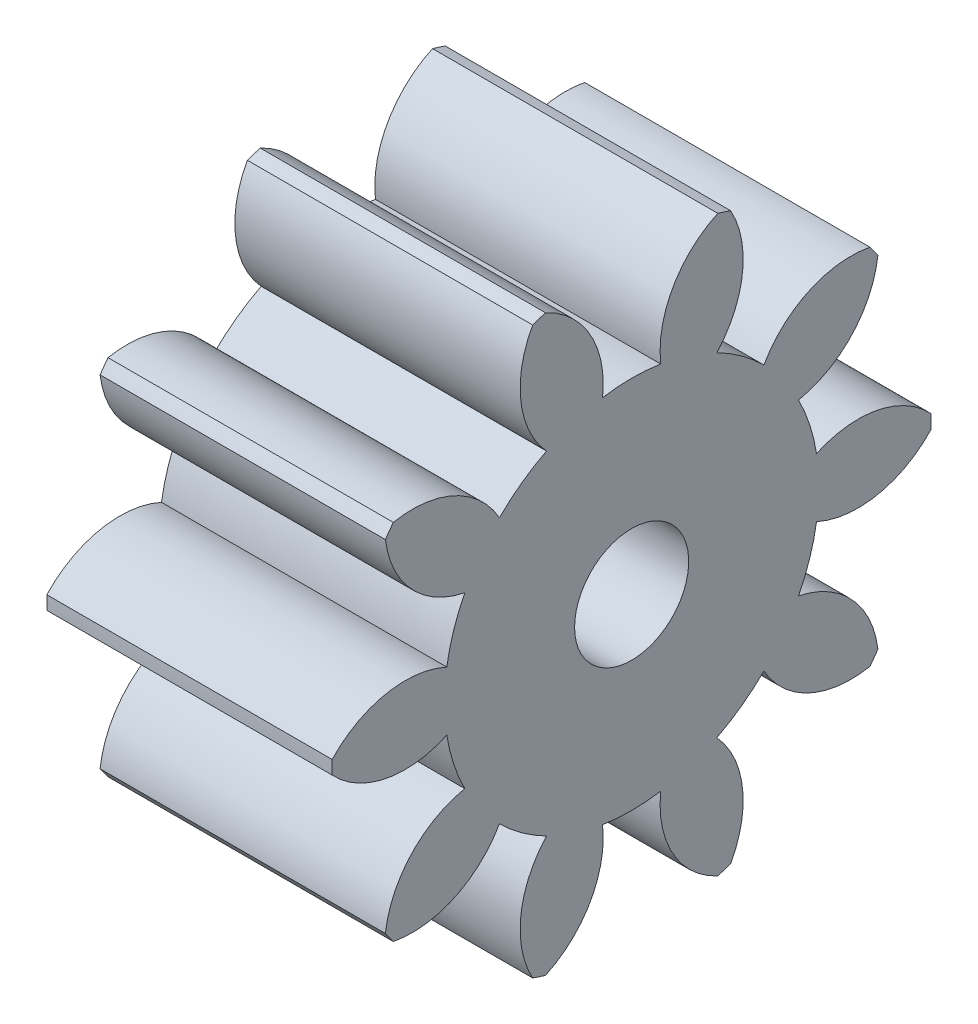
SolidWorks part; units mm, degrees
ref_plane "Plane1" through (0, 0, 0) normal (0, 0, 1) x (1, 0, 0)
ref_plane "Plane2" through (0, 0, 0) normal (0, 1, 0) x (1, 0, 0)
ref_plane "Plane3" through (0, 0, 0) normal (1, 0, 0) x (0, 0, -1)
sketch "HoldingSke" plane through (0, 0, 0) normal (0, 1, 0) x (1, 0, 0)
  line L0 (0, 0) -> (0.5627, -0.0992)
  line L1 (-15, 0) -> (100, 0) construction
  line L2 (0, 0) -> (-2.1039, 2.3779)
  line L3 (0, 0) -> (-11.863, 4.5341)
  line L4 (0, 0) -> (8.5048, 1.4996)
  line L5 (0, 0) -> (-46.8476, -17.4728)
  line L6 (0, 0) -> (-8.2896, -5.593)
  line L7 (-2.1039, 2.3779) -> (8.6586, 51.2059)
  line L8 (-76.2, 54.61) -> (-75.5, 54.61)
  line L9 (-71.009, 38.7566) -> (-53.1078, 45.2721)
  line L10 (-76.2, 71.12) -> (104.1128, 71.12)
  line L11 (0, 0) -> (-10, 0)
  line L12 (-76.2, 101.6) -> (-76.147, 101.6)
  line L13 (24.9733, 27.94) -> (52.9518, 28.4284)
  line L14 (24.9733, 27.94) -> (24.9743, 27.94)
  line L15 (24.9733, 27.94) -> (100.4006, 29.5858)
  line L16 (-63.627, -1.75) -> (-12.827, -1.75)
  circle A0 centre (0, 0) radius 2
  circle A1 centre (0, 0) radius 6.5615
  circle A2 centre (0, 0) radius 37.5
  circle A3 centre (0, 0) radius 2
  dimension "MHD" = 13.123
  dimension "Hub_dia" = 75
  dimension "Bore" = 4
  dimension "MBD" = 4
  dimension "Num_teeth" = 10
  dimension "Pitch" = 0.5714
  dimension "Overall_len" = 50
  dimension "Show_teeth" = 10
  dimension "Thickness" = 10
  dimension "OAL" = 50.0001
  dimension "T_dim" = 0.7
  dimension "Ap" = 20
  dimension "H" = 19.05
  dimension "Pitch_radius" = 180.3128
  dimension "Width" = 10
  dimension "Backlash" = 0.053
  dimension "Addendum_fac" = 1
  dimension "Dedendum_fac" = 1.25
  dimension "Clearance_fac" = 0.25
  dimension "Dedendum_add" = 0.001
  dimension "Module" = 1.75
sketch "BasProSke" plane through (0, 0, 0) normal (0, 1, 0) x (1, 0, 0)
  line L0 (-10, 0) -> (60, 0) construction
  line L1 (0, 0) -> (0, 10.5)
  line L2 (0, 0) -> (10, 0)
  line L3 (10, 0) -> (10, 10.5)
  line L4 (10, 10.5) -> (0, 10.5)
  dimension "Thickness" = 10
  dimension "Diameter" = 21
revolve "Base-Revolve" add sketch "BasProSke" angle 360 about L0
sketch "TooCutSke" plane through (0, 0, 0) normal (1, 0, 0) x (0, 0, -1)
  line L1 (0, 0) -> (0, 107) construction
  line L2 (0, 0) -> (-1.4614, 8.6271) construction
  line L3 (0, 0) -> (-5.35, 16.4656) construction
  line L4 (-1.4614, 8.6271) -> (-2.675, 8.2328) construction
  arc A0 (1.0196, 6.4818) -> (-1.0196, 6.4818) centre (0, 0) ccw
  arc A1 (3.0536, 10.0727) -> (-3.0536, 10.0727) centre (0, 0) ccw
  circle A2 centre (0, 0) radius 8.75 construction
  circle A3 centre (0, 0) radius 8.2223 construction
  arc A4 (-1.0196, 6.4818) -> (-3.0536, 10.0727) centre (-4.4964, 6.8839) ccw
  arc A5 (3.0536, 10.0727) -> (1.0196, 6.4818) centre (4.4964, 6.8839) ccw
  dimension "Root_dia" = 13.123
  dimension "Overcut_dia" = 21.0508
  dimension "Pitch_dia" = 17.5
  dimension "Base_dia" = 16.4446
  dimension "Flank_rad" = 3.5
  dimension "Half_ang" = 18
  dimension "Half_CT" = 1.2761
extrude "ToothCut" cut sketch "TooCutSke" along normal through all
fillet "Breaks" [suppressed] radius 0.035
fillet "RootFillets" [suppressed] radius 0.4385
pattern_circular "TeethCuts" count 10 every 36 about axis through (-10, 0, 0) along (1, 0, 0) of "ToothCut", "RootFillets", "Breaks"
sketch "HubNeaOneSke" plane through (0, 0, 0) normal (-1, 0, 0) x (0, 0, 1)
  circle A0 centre (0, 0) radius 6.5615
  dimension "Diameter" = 13.123
extrude "HubNearOne" [suppressed] add sketch "HubNeaOneSke" along normal blind 40.0001
sketch "HubNeaBotSke" plane through (0, 0, 0) normal (-1, 0, 0) x (0, 0, 1)
  circle A0 centre (0, 0) radius 6.5615
  dimension "Diameter" = 13.123
extrude "HubNearBoth" [suppressed] add sketch "HubNeaBotSke" along normal blind 20
ref_plane "FarPln" through (10, 0, 0) normal (1, 0, 0) x (0, 0, -1)
sketch "HubFarSke" plane through (10, 0, 0) normal (1, 0, 0) x (0, 0, -1)
  circle A0 centre (0, 0) radius 6.5615
  dimension "Diameter" = 13.123
extrude "HubFar" [suppressed] add sketch "HubFarSke" along normal blind 20
sketch "BorSke" plane through (0, 0, 0) normal (1, 0, 0) x (0, 0, -1)
  circle A0 centre (0, 0) radius 2
  dimension "Diameter" = 4
extrude "Bore" cut sketch "BorSke" along normal mid plane 100.0001
sketch "KeySke" plane through (0, 0, 0) normal (1, 0, 0) x (0, 0, -1)
  line L0 (-0.8, 0) -> (-0.8, 2.7)
  line L1 (-0.8, 2.7) -> (0.8, 2.7)
  line L2 (0.8, 2.7) -> (0.8, 0)
  line L3 (0, 0) -> (0, 34) construction
  line L4 (-0.8, 0) -> (0.8, 0)
  dimension "Offset" = 2.7
  dimension "Width" = 1.6
extrude "Keyway" [suppressed] cut sketch "KeySke" along normal mid plane 100.0001
pattern_circular "Keyway2" [suppressed] count 2 every 90 about axis through (-10, 0, 0) along (1, 0, 0)
scale "Scale1" scale about centroid uniform scaling yes scale factor 0.95
equation "' \"Module@HoldingSke\" = 6.35"
equation "' \"Num_teeth@HoldingSke\" = 12"
equation "' \"Ap@HoldingSke\" =  20"
equation "' \"Ap@HoldingSke\" = 20"
equation "' \"Width@HoldingSke\" = 0.5 * 25.4"
equation "' \"Hub_dia@HoldingSke\"= 1 * 25.4"
equation "' \"Hub_dia@HoldingSke\" = 1 * 25.4"
equation "' \"Overall_len@HoldingSke\" = 1.0 * 25.4"
equation "' \"Bore@HoldingSke\" = 0.75 * 25.4"
equation "' \"T_dim@HoldingSke\" = 0.1 * 25.4"
equation "' \"Width@KeySke\" = 0.25 * 25.4"
equation "' \"Show_teeth@HoldingSke\" = 13"
equation "' \"Backlash@HoldingSke\" = 0.009 * 25.4"
equation "' \"Addendum_fac@HoldingSke\" = 1.0"
equation "' \"Dedendum_fac@HoldingSke\" = 1.25"
equation "' \"Dedendum_add@HoldingSke\" = 0.00005 * 25.4"
equation "' \"Clearance_fac@HoldingSke\" = 0.25"
equation "\"Pitch@HoldingSke\" = 1 / \"Module@HoldingSke\""
equation "\"Overcut_dia@TooCutSke\" = (\"Num_teeth@HoldingSke\" + 2 * \"Addendum_fac@HoldingSke\") / \"Pitch@HoldingSke\" + 0.002 * 25.4"
equation "\"Pitch_dia@TooCutSke\" = \"Num_teeth@HoldingSke\" / \"Pitch@HoldingSke\""
equation "\"Base_dia@TooCutSke\" = \"Num_teeth@HoldingSke\" / \"Pitch@HoldingSke\" * cos((\"Ap@HoldingSke\"  * 3.14159265 / 180))"
equation "\"Root_dia@TooCutSke\" = (\"Num_teeth@HoldingSke\" + 2) / \"Pitch@HoldingSke\" - 2 * (\"Addendum_fac@HoldingSke\" + \"Dedendum_fac@HoldingSke\") / \"Pitch@HoldingSke\" - \"Dedendum_add@HoldingSke\" * 2"
equation "\"Half_ang@TooCutSke\" = 180 / \"Num_teeth@HoldingSke\""
equation "\"Half_CT@TooCutSke\" = \"Num_teeth@HoldingSke\" / \"Pitch@HoldingSke\" * sin((3.14159265 / 2 / \"Num_teeth@HoldingSke\")) / 2 - 7 * \"Backlash@HoldingSke\" / 4"
equation "\"Flank_rad@TooCutSke\" = \"Num_teeth@HoldingSke\" / \"Pitch@HoldingSke\" / 5"
equation "\"Radius@RootFillets\" = \"Clearance_fac@HoldingSke\" / \"Pitch@HoldingSke\" + \"Dedendum_add@HoldingSke\""
equation "\"Break_rad@Breaks\" = 0.02 / \"Pitch@HoldingSke\""
equation "\"Thickness@HoldingSke\" = \"Width@HoldingSke\""
equation "\"OAL@HoldingSke\" = \"Thickness@HoldingSke\""
equation "\"MHD@HoldingSke\" = (\"Num_teeth@HoldingSke\" + 2) / \"Pitch@HoldingSke\" - 2 * (\"Addendum_fac@HoldingSke\" + \"Dedendum_fac@HoldingSke\")  / \"Pitch@HoldingSke\" - \"Dedendum_add@HoldingSke\" * 2"
equation "\"MBD@HoldingSke\" = (\"Num_teeth@HoldingSke\" + 2) / \"Pitch@HoldingSke\" - 2 * (\"Addendum_fac@HoldingSke\" + \"Dedendum_fac@HoldingSke\")  / \"Pitch@HoldingSke\" - \"Dedendum_add@HoldingSke\" * 2 - 0.002 * 25.4"
equation "\"MHD@HoldingSke\" = ((sgn( \"MHD@HoldingSke\" - \"Hub_dia@HoldingSke\" )-1)*( \"MHD@HoldingSke\" - \"Hub_dia@HoldingSke\" ))/-2+ \"Hub_dia@HoldingSke\""
equation "\"MBD@HoldingSke\" = ((sgn( \"MBD@HoldingSke\" - \"Bore@HoldingSke\" )-1)*( \"MBD@HoldingSke\" - \"Bore@HoldingSke\" ))/-2+ \"Bore@HoldingSke\""
equation "\"OAL@HoldingSke\" = ((sgn( \"OAL@HoldingSke\" - \"Overall_len@HoldingSke\" )+1)*( \"OAL@HoldingSke\" - \"Overall_len@HoldingSke\" ))/2 + \"Overall_len@HoldingSke\" + 0.000002 * 25.4"
equation "\"Num_teeth@TeethCuts\" = int( \"Show_teeth@HoldingSke\" ) + 1"
equation "\"Num_teeth@TeethCuts\" = ((sgn( \"Num_teeth@TeethCuts\" - \"Num_teeth@HoldingSke\" )-1)*( \"Num_teeth@TeethCuts\" - \"Num_teeth@HoldingSke\" ))/-2+ \"Num_teeth@HoldingSke\""
equation "\"Num_teeth@TeethCuts\" = ((sgn( \"Num_teeth@TeethCuts\" - 2.0)+1)*( \"Num_teeth@TeethCuts\" - 2.0))/2 +2.0"
equation "\"Angle@TeethCuts\" = 360.0 / \"Num_teeth@HoldingSke\""
equation "\"Diameter@BasProSke\" = (\"Num_teeth@HoldingSke\" + 2 * \"Addendum_fac@HoldingSke\") / \"Pitch@HoldingSke\""
equation "\"Thickness@BasProSke\"  = \"Thickness@HoldingSke\""
equation "' \"Fillet_rad@BasProSke\" =  \"Thickness@HoldingSke\" * 0.05"
equation "' \"Fillet_rad@BasProSke\" = \"Thickness@HoldingSke\" * 0.05"
equation "\"MHD@HoldingSke\" = ((sgn( \"MHD@HoldingSke\" - \"Root_dia@TooCutSke\" )-1)*( \"MHD@HoldingSke\" - \"Root_dia@TooCutSke\" ))/-2+ \"Root_dia@TooCutSke\""
equation "\"Diameter@HubNeaOneSke\" = \"MHD@HoldingSke\""
equation "\"Length@HubNearOne\" = \"OAL@HoldingSke\" - \"Thickness@BasProSke\""
equation "\"Diameter@HubNeaBotSke\" = \"MHD@HoldingSke\""
equation "\"Length@HubNearBoth\" = ( \"OAL@HoldingSke\" - \"Thickness@BasProSke\" ) / 2.0"
equation "\"Thickness@FarPln\" = \"Thickness@BasProSke\""
equation "\"Diameter@HubFarSke\" = \"MHD@HoldingSke\""
equation "\"Length@HubFar\" = ( \"OAL@HoldingSke\" - \"Thickness@BasProSke\" ) / 2.0"
equation "\"Diameter@BorSke\" = \"MBD@HoldingSke\""
equation "\"D1@Bore\" = \"OAL@HoldingSke\" * 2.0"
equation "\"D1@Keyway\" = \"OAL@HoldingSke\" * 2.0"
equation "\"Offset@KeySke\" = \"T_dim@HoldingSke\" + \"MBD@HoldingSke\" / 2.0"
